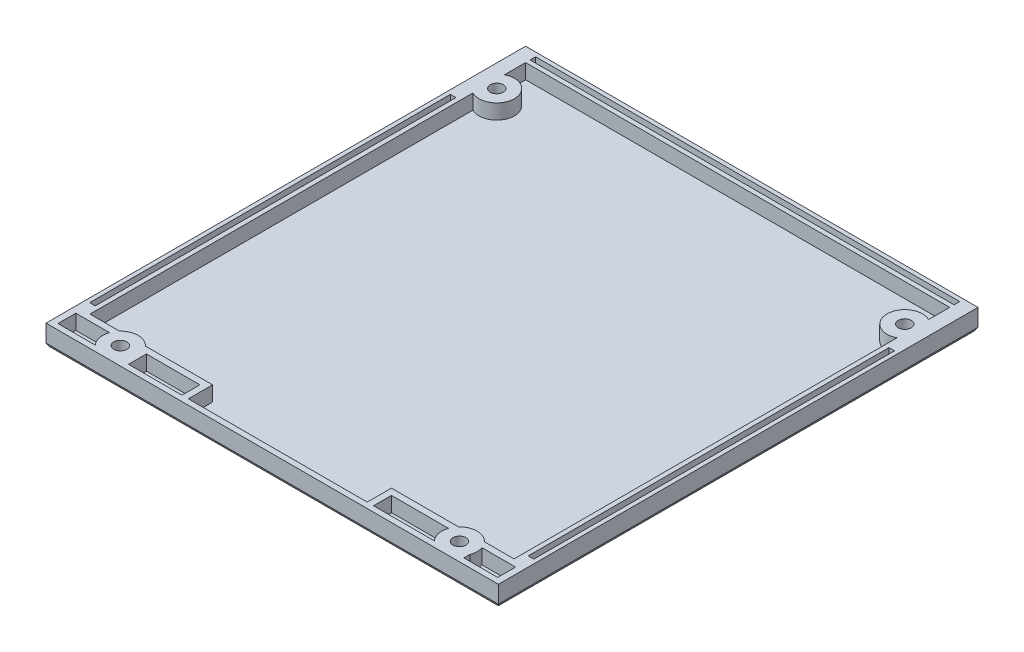
SolidWorks part; units mm, degrees
ref_plane "Спереди" through (0, 0, 0) normal (0, 0, 1) x (1, 0, 0)
ref_plane "Сверху" through (0, 0, 0) normal (0, 1, 0) x (1, 0, 0)
ref_plane "Справа" through (0, 0, 0) normal (1, 0, 0) x (0, 0, -1)
sketch "Эскиз1" plane through (0, 0, 0) normal (0, 1, 0) x (1, 0, 0)
  line L0 (0, 0) -> (0, 128.7)
  line L1 (0, 128.7) -> (121.4, 128.7)
  line L2 (121.4, 128.7) -> (121.4, 0)
  line L3 (121.4, 0) -> (0, 0)
  dimension "D1" = 128.7
  dimension "D2" = 121.4
extrude "Бобышка-Вытянуть1" add sketch "Эскиз1" along normal blind 1.5
sketch "Эскиз2" plane through (0, 1.5, 0) normal (0, 1, 0) x (1, 0, 0)
  line L0 (0, 8) -> (0, 128.7)
  line L1 (0, 128.7) -> (0, 0) construction
  line L2 (0, 128.7) -> (121.4, 128.7)
  line L3 (121.4, 128.7) -> (0, 128.7) construction
  line L4 (121.4, 128.7) -> (121.4, 8)
  line L5 (121.4, 0) -> (121.4, 128.7) construction
  line L6 (121.4, 8) -> (117.6, 8)
  line L7 (117.6, 8) -> (117.6, 124.9)
  line L8 (117.6, 124.9) -> (3.8, 124.9)
  line L9 (3.8, 124.9) -> (3.8, 8)
  line L10 (3.8, 8) -> (0, 8)
  line L11 (0, 0) -> (121.4, 0) construction
  dimension "D1" = 8
  dimension "D2" = 3.8
  dimension "D3" = 3.8
  dimension "D4" = 3.8
extrude "Бобышка-Вытянуть2" add sketch "Эскиз2" along normal blind 2
sketch "Эскиз3" plane through (0, 3.5, 0) normal (0, 1, 0) x (1, 0, 0)
  line L0 (0, 8) -> (3.8, 8)
  line L1 (3.8, 8) -> (3.8, 124.9)
  line L2 (3.8, 124.9) -> (117.6, 124.9)
  line L3 (117.6, 124.9) -> (117.6, 8)
  line L4 (117.6, 8) -> (121.4, 8)
  line L5 (121.4, 8) -> (121.4, 128.7)
  line L6 (121.4, 128.7) -> (0, 128.7)
  line L7 (0, 128.7) -> (0, 8)
  line L8 (1.1, 10.6) -> (2.6, 10.6)
  line L9 (2.6, 10.6) -> (2.6, 107.4)
  line L10 (2.6, 107.4) -> (1.1, 107.4)
  line L11 (1.1, 107.4) -> (1.1, 10.6)
  line L12 (3.8, 127.6) -> (3.8, 126.1)
  line L13 (3.8, 126.1) -> (117.6, 126.1)
  line L14 (117.6, 126.1) -> (117.6, 127.6)
  line L15 (117.6, 127.6) -> (3.8, 127.6)
  line L16 (118.8, 107.4) -> (120.3, 107.4)
  line L17 (120.3, 107.4) -> (120.3, 10.6)
  line L18 (120.3, 10.6) -> (118.8, 10.6)
  line L19 (118.8, 107.4) -> (118.8, 10.6)
  dimension "D1" = 1.1
  dimension "D2" = 1.1
  dimension "D3" = 1.1
  dimension "D4" = 1.5
  dimension "D5" = 1.5
  dimension "D6" = 1.5
  dimension "D7" = 2.6
  dimension "D8" = 21.3
  dimension "D9" = 3.8
  dimension "D10" = 3.8
  dimension "D11" = 21.3
  dimension "D12" = 2.6
extrude "Бобышка-Вытянуть3" add sketch "Эскиз3" along normal blind 2
sketch "Эскиз4" plane through (0, 5.5, 0) normal (0, 1, 0) x (1, 0, 0)
  line L0 (0, 8) -> (0, 12.75)
  line L1 (0, 128.7) -> (6, 128.7)
  line L2 (121.4, 128.7) -> (121.4, 105.2)
  line L3 (121.4, 8) -> (117.6, 8)
  line L4 (117.6, 8) -> (117.6, 12.75)
  line L5 (117.6, 124.9) -> (115.4, 124.9)
  line L6 (3.8, 124.9) -> (3.8, 105.2)
  line L7 (3.8, 8) -> (0, 8)
  line L8 (0, 12.75) -> (1.1, 12.75)
  line L9 (117.6, 12.75) -> (118.8, 12.75)
  line L10 (0, 105.2) -> (1.1, 105.2)
  line L11 (6, 128.7) -> (6, 127.6)
  line L12 (115.4, 128.7) -> (115.4, 127.6)
  line L13 (117.6, 105.2) -> (118.8, 105.2)
  line L14 (1.1, 12.75) -> (1.1, 10.6)
  line L15 (1.1, 107.4) -> (1.1, 10.6) construction
  line L16 (1.1, 10.6) -> (2.6, 10.6)
  line L17 (2.6, 10.6) -> (2.6, 12.75)
  line L18 (2.6, 10.6) -> (2.6, 107.4) construction
  line L19 (118.8, 12.75) -> (118.8, 10.6)
  line L20 (118.8, 107.4) -> (118.8, 10.6) construction
  line L21 (118.8, 10.6) -> (120.3, 10.6)
  line L22 (120.3, 10.6) -> (120.3, 12.75)
  line L23 (120.3, 10.6) -> (120.3, 107.4) construction
  line L24 (1.1, 105.2) -> (1.1, 107.4)
  line L25 (1.1, 107.4) -> (2.6, 107.4)
  line L26 (2.6, 107.4) -> (2.6, 105.2)
  line L27 (6, 127.6) -> (3.8, 127.6)
  line L28 (117.6, 127.6) -> (3.8, 127.6) construction
  line L29 (3.8, 127.6) -> (3.8, 126.1)
  line L30 (3.8, 126.1) -> (6, 126.1)
  line L31 (3.8, 126.1) -> (117.6, 126.1) construction
  line L32 (115.4, 127.6) -> (117.6, 127.6)
  line L33 (117.6, 127.6) -> (117.6, 126.1)
  line L34 (117.6, 126.1) -> (115.4, 126.1)
  line L35 (3.8, 126.1) -> (117.6, 126.1) construction
  line L36 (120.3, 105.2) -> (120.3, 107.4)
  line L37 (120.3, 10.6) -> (120.3, 107.4) construction
  line L38 (120.3, 107.4) -> (118.8, 107.4) construction
  line L39 (120.3, 107.4) -> (118.8, 107.4) construction
  line L40 (120.3, 107.4) -> (118.8, 107.4)
  line L41 (118.8, 107.4) -> (118.8, 105.2)
  line L42 (117.6, 105.2) -> (117.6, 124.9)
  line L43 (121.4, 12.75) -> (121.4, 8)
  line L44 (6, 124.9) -> (3.8, 124.9)
  line L45 (115.4, 128.7) -> (121.4, 128.7)
  line L46 (3.8, 12.75) -> (3.8, 8)
  line L47 (0, 105.2) -> (0, 128.7)
  line L48 (2.6, 12.75) -> (3.8, 12.75)
  line L49 (120.3, 12.75) -> (121.4, 12.75)
  line L50 (120.3, 105.2) -> (121.4, 105.2)
  line L51 (115.4, 126.1) -> (115.4, 124.9)
  line L52 (6, 126.1) -> (6, 124.9)
  line L53 (2.6, 105.2) -> (3.8, 105.2)
  dimension "D1" = 4.75
  dimension "D2" = 23.5
  dimension "D3" = 6
  dimension "D4" = 6
  dimension "D5" = 23.5
  dimension "D6" = 4.75
sketch "Эскиз5" plane through (0, 1.5, 0) normal (0, 1, 0) x (1, 0, 0)
  line L0 (0, 8) -> (0, 0)
  line L1 (0, 0) -> (121.4, 0)
  line L2 (121.4, 0) -> (121.4, 8)
  line L3 (121.4, 8) -> (0, 8)
  line L4 (1.7, 6.3) -> (1.7, 1.5)
  line L5 (1.7, 1.5) -> (14.15, 1.5)
  line L6 (119.7, 1.5) -> (119.7, 6.3)
  line L7 (119.7, 6.3) -> (110.65, 6.3)
  line L8 (110.65, 6.3) -> (110.65, 1.5)
  line L9 (14.15, 6.3) -> (14.15, 1.5)
  line L10 (104.15, 6.3) -> (104.15, 1.5)
  line L11 (20.65, 6.3) -> (20.65, 1.5)
  line L15 (14.15, 6.3) -> (1.7, 6.3)
  line L18 (35, 6.3) -> (20.65, 6.3)
  line L28 (36.7, 1.5) -> (84.7, 1.5)
  line L29 (84.7, 6.3) -> (36.7, 6.3)
  line L33 (104.15, 6.3) -> (86.4, 6.3)
  line L34 (110.65, 1.5) -> (119.7, 1.5)
  line L35 (20.65, 1.5) -> (35, 1.5)
  line L36 (121.4, 4) -> (107.4, 4) construction
  line L37 (84.7, 6.3) -> (84.7, 1.5)
  line L38 (86.4, 6.3) -> (86.4, 1.5)
  line L40 (86.4, 1.5) -> (104.15, 1.5)
  line L41 (35, 6.3) -> (35, 1.5)
  line L42 (36.7, 6.3) -> (36.7, 1.5)
  line L43 (60.7, 1.5) -> (60.7, 0) construction
  point P43 (17.4, 4)
  dimension "D1" = 1.5
  dimension "D2" = 1.7
  dimension "D3" = 1.7
  dimension "D4" = 1.7
  dimension "D5" = 6.5
  dimension "D6" = 48
  dimension "D7" = 1.7
  dimension "D10" = 6.5
  dimension "D11" = 14
  dimension "D12" = 3.25
  dimension "D13" = 90
  dimension "D14" = 3.25
  dimension "D21" = 1.7
extrude "Бобышка-Вытянуть5" add sketch "Эскиз5" along normal blind 4
sketch "Эскиз6" plane through (0, 0, 0) normal (0, -1, 0) x (1, 0, 0)
  line L0 (121.4, 0) -> (121.4, -128.7) construction
  line L1 (0, 0) -> (121.4, 0) construction
  line L2 (121.4, -128.7) -> (0, -128.7) construction
  line L3 (0, -128.7) -> (0, 0) construction
  line L4 (0, -128.7) -> (0, 0) construction
  circle A0 centre (106.2, -4.75) radius 3.15
  circle A1 centre (15.2, -4.75) radius 3.15
  circle A2 centre (115.45, -115) radius 3.15
  circle A3 centre (5.95, -115) radius 3.15
  dimension "D3" = 6.3
  dimension "D1" = 15.2
  dimension "D2" = 4.75
  dimension "D4" = 15.2
  dimension "D5" = 5.95
  dimension "D6" = 13.7
  dimension "D7" = 5.95
sketch "Эскиз7" plane through (0, 1.5, 0) normal (0, 1, 0) x (1, 0, 0)
  circle A0 centre (5.95, 115) radius 4.75
  circle A1 centre (115.45, 115) radius 4.75
  circle A2 centre (15.2, 4.75) radius 4.75
  circle A3 centre (106.2, 4.75) radius 4.75
  dimension "D1" = 9.5
sketch "Эскиз8" plane through (0, 0, 0) normal (0, -1, 0) x (1, 0, 0)
  circle A0 centre (15.2, -4.75) radius 1.75
  circle A1 centre (106.2, -4.75) radius 1.75
  circle A2 centre (5.95, -115) radius 1.75
  circle A3 centre (115.45, -115) radius 1.75
  circle A4 centre (106.2, -4.75) radius 3.15 construction
  circle A5 centre (5.95, -115) radius 3.15 construction
  circle A6 centre (115.45, -115) radius 3.15 construction
  circle A8 centre (15.2, -4.75) radius 3.15 construction
  dimension "D1" = 3.5
extrude "Бобышка-Вытянуть10" add sketch "Эскиз7" along normal blind 4
extrude "Вырез-Вытянуть3" cut sketch "Эскиз8" against normal blind 5.5
chamfer "Фаска1" distance 1.6 angle 45 4 edges at (106.2, 0, -6.5) (15.2, 0, -6.5) (5.95, 0, -116.75) (115.45, 0, -116.75)
sketch "Эскиз10" plane through (0, 5.5, 0) normal (0, 1, 0) x (1, 0, 0)
  line L0 (102.7359, 8) -> (18.6641, 8) construction
  line L1 (36.7, 8) -> (84.7, 8)
  line L2 (36.7, 8) -> (36.7, 1.5)
  line L3 (36.7, 1.5) -> (84.7, 1.5)
  line L4 (84.7, 8) -> (84.7, 1.5)
  line L5 (36.7, 1.5) -> (84.7, 1.5) construction
  line L6 (60.7, 1.5) -> (60.7, 0) construction
  line L7 (0, 0) -> (121.4, 0) construction
  dimension "D1" = 48
extrude "Вырез-Вытянуть4" cut sketch "Эскиз10" against normal blind 4
chamfer "Фаска2" distance 0.5 angle 60 4 edges at (121.4, 0, -64.35) (60.7, 0, 0) (60.7, 0, -128.7) (0, 0, -64.35)
